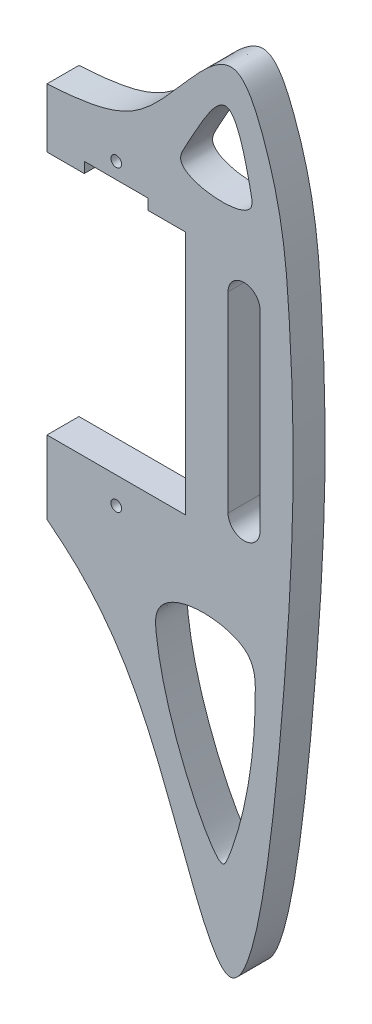
SolidWorks part; units mm, degrees
ref_plane "Front Plane" through (0, 0, 0) normal (0, 0, 1) x (1, 0, 0)
ref_plane "Top Plane" through (0, 0, 0) normal (0, 1, 0) x (1, 0, 0)
ref_plane "Right Plane" through (0, 0, 0) normal (1, 0, 0) x (0, 0, -1)
sketch "Sketch1" plane through (0, 0, 0) normal (0, 0, 1) x (1, 0, 0)
  line L0 (0, 35.9254) -> (0, -32.0186) construction
  line L1 (-11.5, 41.9239) -> (-11.5, -20.9458) construction
  line L2 (-6.5, 24.5905) -> (6.5, 24.5905)
  line L3 (-6.5, 24.5905) -> (-6.5, 1.5905)
  line L4 (-6.5, 1.5905) -> (-3, 1.5905)
  line L5 (6.5, 24.5905) -> (6.5, 1.5905)
  line L6 (-6.5, 24.5905) -> (6.5, 1.5905) construction
  line L7 (-6.5, 1.5905) -> (6.5, 24.5905) construction
  line L8 (3, 1.5905) -> (6.5, 1.5905)
  line L9 (-3, 1.5905) -> (-3, 0.5905)
  line L10 (-3, 0.5905) -> (3, 0.5905)
  line L11 (3, 1.5905) -> (3, 0.5905)
  line L12 (-3, 2.5905) -> (3, 0.5905) construction
  line L13 (-3, 0.5905) -> (3, 2.5905) construction
  line L14 (-11.5, 29.9892) -> (-11.5, -2.003)
  circle A0 centre (0, 27.0905) radius 0.5
  circle A1 centre (0, -0.9095) radius 0.5
  spline S0 degree 3 poles (-11.5, 29.9892) (0.931, 30.144) (1.8648, 31.5363) (11.1826, 42.0998) (15.4635, 32.6126) (16.8275, 16.7498) (16.812, -1.6656) (11.9215, -45.3547) (2.8011, -13.0475) (-4.5223, -6.0753) (-11.5, -2.003) knots 0 0 0 0 0.137545 0.178056 0.211384 0.308424 0.54242 0.718102 0.845349 1 1 1 1
  point P3 (0, 13.0905)
  point P8 (0, 1.5905)
  dimension "D5" = 1
  dimension "D1" = 13
  dimension "D2" = 23
  dimension "D3" = 2
  dimension "D4" = 6
  dimension "D6" = 2.5
  dimension "D7" = 2.5
  dimension "D8" = 5
extrude "Boss-Extrude1" add sketch "Sketch1" along normal blind 3
sketch "Sketch2" plane through (0, 0, 3) normal (0, 0, 1) x (1, 0, 0)
  line L1 (-3, 0.5905) -> (3, 0.5905)
  line L2 (-3, 0.5905) -> (-3, 1.5905)
  line L3 (-3, 1.5905) -> (3, 1.5905)
  line L4 (3, 0.5905) -> (3, 1.5905)
extrude "Boss-Extrude2" add sketch "Sketch2" against normal blind 3
sketch "Sketch3" plane through (0, 0, 3) normal (0, 0, 1) x (1, 0, 0)
  line L0 (-6.5, 24.5905) -> (-6.5, 30.141)
  line L1 (-6.5, 24.5905) -> (-6.5, -5.2888)
  line L2 (-11.5, 29.9892) -> (-11.5, -2.003) construction
  line L3 (-11.5, 29.9892) -> (-11.5, -2.003)
  line L5 (-11.5, 29.9892) -> (-11.5, -2.003)
  line L6 (-11.5, 29.9892) -> (-11.5, -2.003)
  spline S0 degree 3 poles (-1988.547, 2247.4211) (-101.3446, -192.954) (-21.8024, 74.1052) (11.9215, -45.3547) (16.812, -1.6656) (16.8275, 16.7498) (15.4635, 32.6126) (11.1826, 42.0998) (-28.1867, -2.5332) (95.1543, 129.5192) (-2987.7673, -337.7522) knots -1.234382 -1.234382 -1.234382 -1.234382 0.154651 0.281898 0.45758 0.691576 0.788616 0.821944 0.862455 1.681752 1.681752 1.681752 1.681752 only from (-11.5, -2.003) to (-11.5, 29.9892) construction
  spline S1 degree 3 poles (-11.5, -2.003) (-9.6381, -3.0897) (-7.9869, -4.1587) (-6.5, -5.2888) knots 0 0 0 0 0.041267 0.041267 0.041267 0.041267
  spline S2 degree 3 poles (-6.5, 30.141) (-7.9242, 30.0594) (-9.5711, 30.0132) (-11.5, 29.9892) knots 0.978658 0.978658 0.978658 0.978658 1 1 1 1
  spline S3 degree 3 poles (-3193.965, 3843.2063) (-128.9102, -291.1712) (-26.7846, 91.7536) (11.9215, -45.3547) (16.812, -1.6656) (16.8275, 16.7498) (15.4635, 32.6126) (11.1826, 42.0998) (-34.6315, -9.8397) (141.764, 179.49) (-4963.0333, -648.8493) knots -1.484343 -1.484343 -1.484343 -1.484343 0.154651 0.281898 0.45758 0.691576 0.788616 0.821944 0.862455 1.82796 1.82796 1.82796 1.82796 only from (-11.5, -2.003) to (-11.5, 29.9892)
  spline S4 degree 3 poles (-11.5, -2.003) (-9.6381, -3.0897) (-7.9869, -4.1587) (-6.5, -5.2888) knots 0 0 0 0 0.041267 0.041267 0.041267 0.041267
  spline S5 degree 3 poles (-6.5, 30.141) (-7.9242, 30.0594) (-9.5711, 30.0132) (-11.5, 29.9892) knots 0.978658 0.978658 0.978658 0.978658 1 1 1 1
  spline M4 degree 3 poles (-11.5, -2.003) (-4.5223, -6.0753) (2.8011, -13.0475) (11.9215, -45.3547) (16.812, -1.6656) (16.8275, 16.7498) (15.4635, 32.6126) (11.1826, 42.0998) (1.8648, 31.5363) (0.931, 30.144) (-11.5, 29.9892) knots 0 0 0 0 0.154651 0.281898 0.45758 0.691576 0.788616 0.821944 0.862455 1 1 1 1
  line M5 (-11.5, 29.9892) -> (-11.5, -2.003)
  line M7 (-6.5, 1.5905) -> (-6.5, 24.5905)
  dimension "D1" = 0
extrude "Cut-Extrude1" cut sketch "Sketch3" against normal blind 5 contours L1 L0 M7 M4 M5
sketch "Sketch4" plane through (0, 0, 3) normal (0, 0, 1) x (1, 0, 0)
  line L0 (6.5, 24.5905) -> (-6.5, 24.5905) construction
  line L1 (-3, 23.5905) -> (3, 23.5905)
  line L2 (-3, 23.5905) -> (-3, 25.5905)
  line L3 (-3, 25.5905) -> (3, 25.5905)
  line L4 (3, 23.5905) -> (3, 25.5905)
  line L5 (-3, 23.5905) -> (3, 25.5905) construction
  line L6 (-3, 25.5905) -> (3, 23.5905) construction
  point P0 (0, 24.5905)
  dimension "D1" = 2
  dimension "D2" = 6
extrude "Cut-Extrude2" cut sketch "Sketch4" against normal up to next
sketch "Sketch6" plane through (0, 0, 3) normal (0, 0, 1) x (1, 0, 0)
  spline S0 degree 3 poles (3.3679, -4.9885) (4.2545, -15.4503) (9.526, -26.3058) (11.1955, -23.0361) (13.3027, -15.6737) (12.9469, -5.0042) (3.3679, -4.9885) (4.2545, -15.4503) (9.526, -26.3058) knots -0.227786 -0.155666 -0.017296 0 0.250916 0.333619 0.772214 0.844334 0.982704 1 1.250916 1.333619 1.772214 only from (3.7594, -9.4448) to (3.7594, -9.4448)
extrude "Cut-Extrude3" cut sketch "Sketch6" against normal blind 5
sketch "Sketch8" plane through (0, 0, 3) normal (0, 0, 1) x (1, 0, 0)
  line L0 (12, 21.7388) -> (12, 3.7388) construction
  line L1 (13.5, 21.7388) -> (13.5, 3.7388)
  line L2 (10.5, 21.7388) -> (10.5, 3.7388)
  line L3 (6.5, 1.5905) -> (6.5, 24.5905) construction
  arc A0 (13.5, 21.7388) -> (10.5, 21.7388) centre (12, 21.7388) ccw
  arc A1 (10.5, 3.7388) -> (13.5, 3.7388) centre (12, 3.7388) ccw
  point P2 (12, 12.7388)
  point P7 (10.5, 12.7388)
  dimension "D1" = 4
  dimension "D2" = 3
  dimension "D3" = 18
extrude "Cut-Extrude4" cut sketch "Sketch8" against normal blind 5
sketch "Sketch9" plane through (0, 0, 3) normal (0, 0, 1) x (1, 0, 0)
  spline S0 degree 3 poles (7.6406, 33.524) (10.6467, 39.6601) (12.272, 32.6965) (13.2205, 28.0732) (4.8737, 28.7723) (7.6406, 33.524) (10.6467, 39.6601) (12.272, 32.6965) knots -0.634091 -0.377929 -0.311318 0 0.3005 0.365909 0.622071 0.688682 1 1.3005 1.365909 1.622071 only from (10.3729, 36.6963) to (10.3729, 36.6963)
extrude "Cut-Extrude5" cut sketch "Sketch9" against normal blind 5
